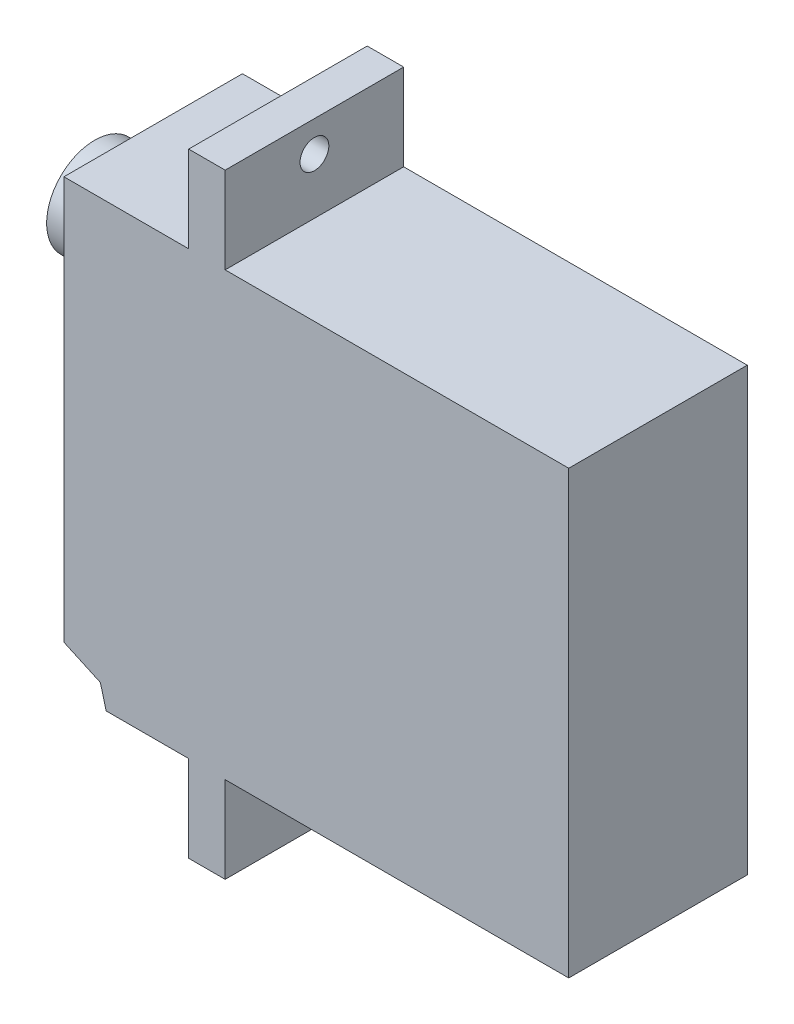
SolidWorks part; units mm, degrees
ref_plane "Front Plane" through (0, 0, 0) normal (0, 0, 1) x (1, 0, 0)
ref_plane "Top Plane" through (0, 0, 0) normal (0, 1, 0) x (1, 0, 0)
ref_plane "Right Plane" through (0, 0, 0) normal (1, 0, 0) x (0, 0, -1)
sketch "Sketch1" plane through (0, 0, 0) normal (0, 0, 1) x (1, 0, 0)
  line L0 (-4.75, 11.5) -> (-4.75, 16)
  line L1 (-10.95, -11.5) -> (-6.65, -11.5)
  line L2 (-13.15, -9.5) -> (-13.15, 11.5)
  line L3 (-13.15, 11.5) -> (-6.65, 11.5)
  line L4 (13.15, -11.5) -> (13.15, 11.5)
  line L5 (-13.15, -11.5) -> (13.15, 11.5) construction
  line L6 (-13.15, 11.5) -> (13.15, -11.5) construction
  line L7 (-4.75, 16) -> (-6.65, 16)
  line L8 (-6.65, 16) -> (-6.65, 11.5)
  line L9 (-4.75, 11.5) -> (13.15, 11.5)
  line L10 (-4.75, -11.5) -> (-4.75, -16)
  line L11 (-4.75, -16) -> (-6.65, -16)
  line L12 (-6.65, -16) -> (-6.65, -11.5)
  line L13 (-4.75, -11.5) -> (13.15, -11.5)
  line L14 (-10.95, -11.5) -> (-11.2512, -10.3669) construction
  line L15 (-11.2512, -10.3669) -> (-13.15, -9.5) construction
  line L16 (-10.95, -11.5) -> (-13.15, -11.5)
  line L17 (-13.15, -11.5) -> (-13.15, -9.5)
  point P0 (0, 0)
  dimension "D1" = 26.3
  dimension "D2" = 23
  dimension "D3" = 32
  dimension "D4" = 6.5
  dimension "D5" = 1.9
  dimension "D6" = 2.2
  dimension "D7" = 2
extrude "Boss-Extrude1" add sketch "Sketch1" along normal mid plane 9.3
sketch "Sketch7" plane through (0, 0, 0) normal (0, 0, 1) x (1, 0, 0)
  line L0 (-11.2512, -10.3669) -> (-13.15, -9.5) construction
  line L1 (-11.2512, -10.3669) -> (-13.15, -9.5)
  line L2 (-13.15, -11.5) -> (-13.15, -9.5) construction
  line L3 (-10.95, -11.5) -> (-13.15, -11.5) construction
  line L4 (-10.95, -11.5) -> (-11.2512, -10.3669) construction
  line L5 (-13.15, -11.5) -> (-13.15, -9.5)
  line L6 (-10.95, -11.5) -> (-13.15, -11.5)
  line L7 (-10.95, -11.5) -> (-11.2512, -10.3669)
extrude "Cut-Extrude4" cut sketch "Sketch7" against normal through all both and the other way through all
sketch "Sketch8" [suppressed] plane through (0, 0, 0) normal (0, 0, 1) x (1, 0, 0)
  line L0 (0, 0) -> (-13.15, 0) construction
  line L1 (-13.15, -11.5) -> (13.15, 11.5) construction
  line L2 (-13.15, -9.5) -> (-13.15, 11.5) construction
  line L3 (-10.95, -11.5) -> (-11.2512, -10.3669) construction
  line L4 (-10.95, -11.5) -> (-11.2512, -10.3669) construction
  line L5 (-10.95, -11.5) -> (-13.15, -11.5) construction
  line L6 (-13.15, -11.5) -> (-13.15, -9.5) construction
  line L7 (-11.2512, -10.3669) -> (-13.15, -9.5) construction
  line L8 (-10.95, -11.5) -> (-13.15, -11.5) construction
  line L9 (-13.15, -11.5) -> (-13.15, -9.5) construction
  line L10 (-11.2512, -10.3669) -> (-13.15, -9.5) construction
  line L11 (-11.2512, 10.3669) -> (-13.15, 9.5)
  line L12 (-13.15, 11.5) -> (-13.15, 9.5)
  line L13 (-10.95, 11.5) -> (-13.15, 11.5)
  line L14 (-10.95, 11.5) -> (-11.2512, 10.3669)
  line L15 (-13.15, 11.5) -> (13.15, -11.5) construction
extrude "Cut-Extrude5" [suppressed] cut sketch "Sketch8" against normal through all both and the other way through all
sketch "Sketch2" plane through (-13.15, 0, 0) normal (-1, 0, 0) x (0, 0, 1)
  line L0 (0, 11.5) -> (0, 6.8) construction
  line L2 (4.65, 11.5) -> (-4.65, 11.5) construction
  circle A0 centre (0, 6.8) radius 2.5
  dimension "D1" = 5
  dimension "D2" = 4.7
sketch "Sketch3" plane through (0, 0, 0) normal (0, 0, 1) x (1, 0, 0)
  line L0 (-13.15, 6.8) -> (-16.2, 6.8)
  line L1 (-16.2, 6.8) -> (-16.2, 9.3)
  line L6 (-16.2, 9.3) -> (-13.15, 9.3)
  line L7 (-13.15, 11.5) -> (-13.15, 6.8) construction
  line L8 (-13.15, 9.3) -> (-13.15, 6.8)
  line L9 (-13.15, 11.5) -> (-13.15, -9.5) construction
  dimension "D2" = 2.5
  dimension "D5" = 3.05
revolve "Revolve1" add sketch "Sketch3" angle 360 about L0
sketch "Sketch4" plane through (-6.65, 0, 0) normal (-1, 0, 0) x (0, 0, 1)
  line L0 (0, 16) -> (0, 14.4) construction
  line L1 (4.65, 16) -> (-4.65, 16) construction
  line L2 (0, 14.4) -> (0, -14.4) construction
  line L3 (0, -14.4) -> (0, -16) construction
  line L4 (4.65, -16) -> (-4.65, -16) construction
  circle A0 centre (0, 14.4) radius 0.75
  circle A1 centre (0, -14.4) radius 0.75
  dimension "D1" = 1.5
  dimension "D2" = 1.6
extrude "Cut-Extrude1" cut sketch "Sketch4" against normal blind 10
sketch "Sketch5" [suppressed] plane through (-17.75, 0, 0) normal (-1, 0, 0) x (0, 0, 1)
  line L0 (-9.3675, 10.3) -> (9.3675, 10.3)
  circle A0 centre (0, 6.8) radius 3.5 construction
  circle A1 centre (0, 6.8) radius 10
  arc A2 (9.3675, 10.3) -> (-9.3675, 10.3) centre (0, 6.8) ccw
  circle A3 centre (0, 6.8) radius 3.5 construction
  dimension "D1" = 0
extrude "Cut-Extrude2" [suppressed] cut sketch "Sketch5" against normal up to surface (1.7 mm away)
sketch "Sketch6" [suppressed] plane through (-17.75, 0, 0) normal (-1, 0, 0) x (0, 0, 1)
  line L0 (9.3675, 3.3) -> (-9.3675, 3.3)
  circle A0 centre (0, 6.8) radius 3.5 construction
  circle A1 centre (0, 6.8) radius 10
  arc A2 (-9.3675, 3.3) -> (9.3675, 3.3) centre (0, 6.8) ccw
  circle A3 centre (0, 6.8) radius 3.5 construction
  dimension "D1" = 0
extrude "Cut-Extrude3" [suppressed] cut sketch "Sketch6" against normal up to next
surface "Surface-Offset1" [suppressed] parameters "D1"=0.2
surface "Surface-Extend2" [suppressed] parameters "D1"=2.4
surface "Surface-Plane1" [suppressed]
surface "Surface-Knit1" [suppressed]
surface "Surface-Fill1" [suppressed]
surface "Surface-Fill2" [suppressed]
surface "Surface-Fill3" [suppressed]
surface "Surface-Fill4" [suppressed]
surface "Surface-Fill5" [suppressed]
surface "Surface-Knit2" [suppressed]
